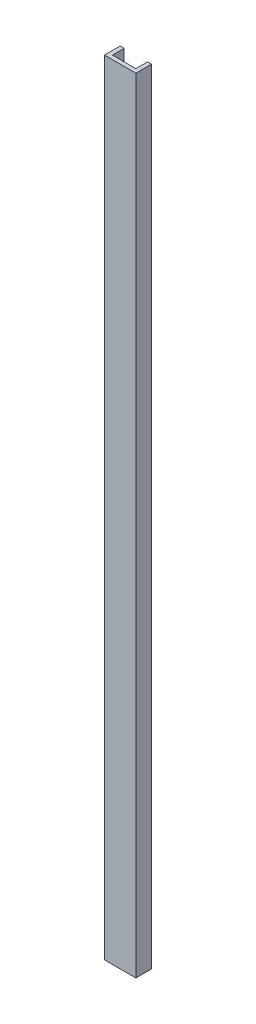
SolidWorks part; units mm, degrees
material "6061 Alloy"
ref_plane "Front Plane" through (0, 0, 0) normal (0, 0, 1) x (1, 0, 0)
ref_plane "Top Plane" through (0, 0, 0) normal (0, 1, 0) x (1, 0, 0)
ref_plane "Right Plane" through (0, 0, 0) normal (1, 0, 0) x (0, 0, -1)
sketch "Sketch3" plane through (0, 0, 0) normal (0, 1, 0) x (1, 0, 0)
  line L1 (-41.0115, -80.5761) -> (-15.6115, -80.5761)
  line L2 (-41.0115, -80.5761) -> (-41.0115, -93.2761)
  line L3 (-41.0115, -93.2761) -> (-15.6115, -93.2761)
  line L4 (-15.6115, -80.5761) -> (-15.6115, -93.2761)
  line L5 (-37.8365, -80.5761) -> (-18.7865, -80.5761)
  line L6 (-37.8365, -80.5761) -> (-37.8365, -90.1011)
  line L7 (-37.8365, -90.1011) -> (-18.7865, -90.1011)
  line L8 (-18.7865, -80.5761) -> (-18.7865, -90.1011)
  dimension "D1" = 12.7
  dimension "D2" = 25.4
  dimension "D3" = 3.175
  dimension "D4" = 3.175
  dimension "D5" = 3.175
extrude "Boss-Extrude2" add sketch "Sketch3" along normal blind 635 contours L1 L8 L7 L6 L2 L3 L4
